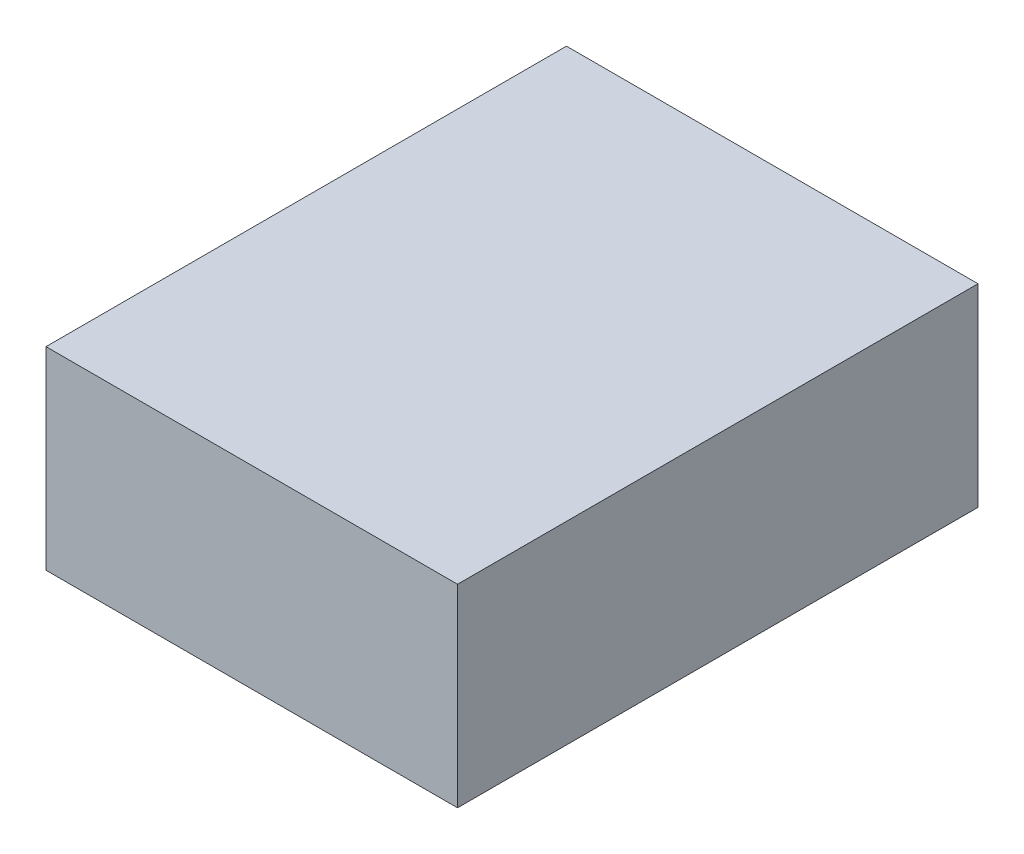
SolidWorks part; units mm, degrees
ref_plane "Front Plane" through (0, 0, 0) normal (0, 0, 1) x (1, 0, 0)
ref_plane "Top Plane" through (0, 0, 0) normal (0, 1, 0) x (1, 0, 0)
ref_plane "Right Plane" through (0, 0, 0) normal (1, 0, 0) x (0, 0, -1)
sketch "Sketch1" plane through (0, 0, 0) normal (0, 1, 0) x (1, 0, 0)
  line L1 (-170, 215) -> (170, 215)
  line L2 (-170, 215) -> (-170, -215)
  line L3 (-170, -215) -> (170, -215)
  line L4 (170, 215) -> (170, -215)
  line L5 (-170, 215) -> (170, -215) construction
  line L6 (-170, -215) -> (170, 215) construction
  point P0 (0, 0)
  dimension "D1" = 340
  dimension "D2" = 430
extrude "Boss-Extrude1" add sketch "Sketch1" along normal blind 160
